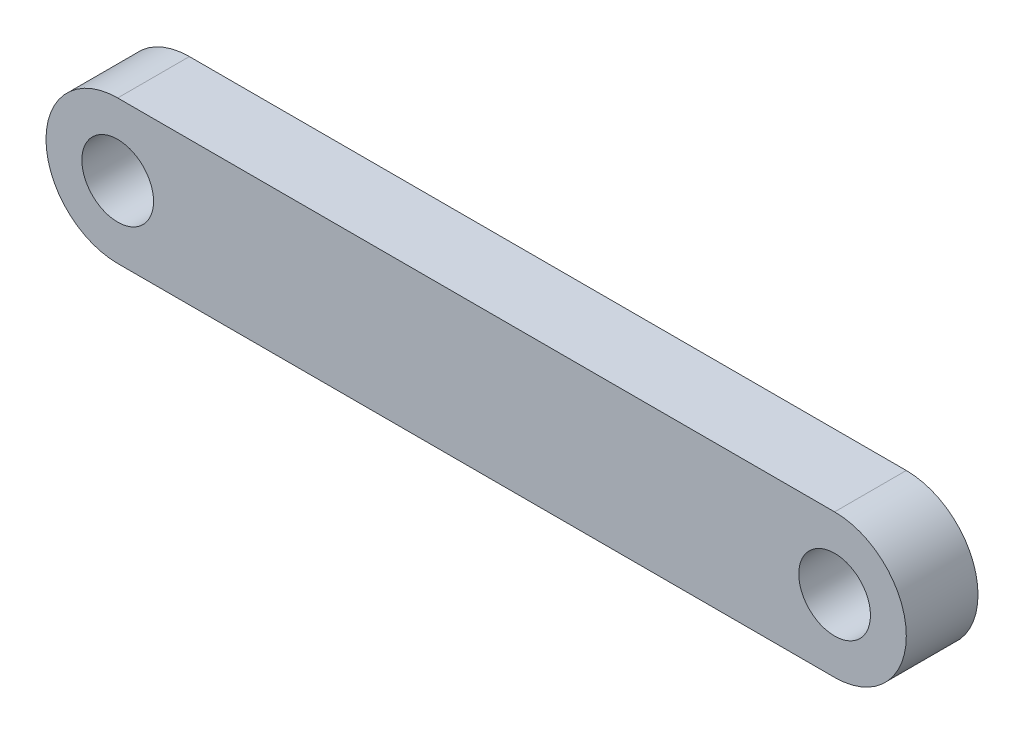
SolidWorks part; units mm, degrees
ref_plane "Plane1" through (0, 0, 0) normal (0, 0, 1) x (1, 0, 0)
ref_plane "Plane2" through (0, 0, 0) normal (0, 1, 0) x (1, 0, 0)
ref_plane "Plane3" through (0, 0, 0) normal (1, 0, 0) x (0, 0, -1)
other "Configuration Table"
sketch "Sketch1" plane through (0, 0, 0) normal (0, 0, 1) x (1, 0, 0)
  line L0 (50, 10) -> (-50, 10)
  line L1 (-50, -10) -> (50, -10)
  arc A0 (50, -10) -> (50, 10) centre (50, 0) ccw
  arc A1 (-50, 10) -> (-50, -10) centre (-50, 0) ccw
  circle A2 centre (50, 0) radius 5
  circle A3 centre (-50, 0) radius 5
  dimension "D1" = 10
  dimension "D2" = 10
extrude "Base-Extrude" add sketch "Sketch1" along normal mid plane 10
